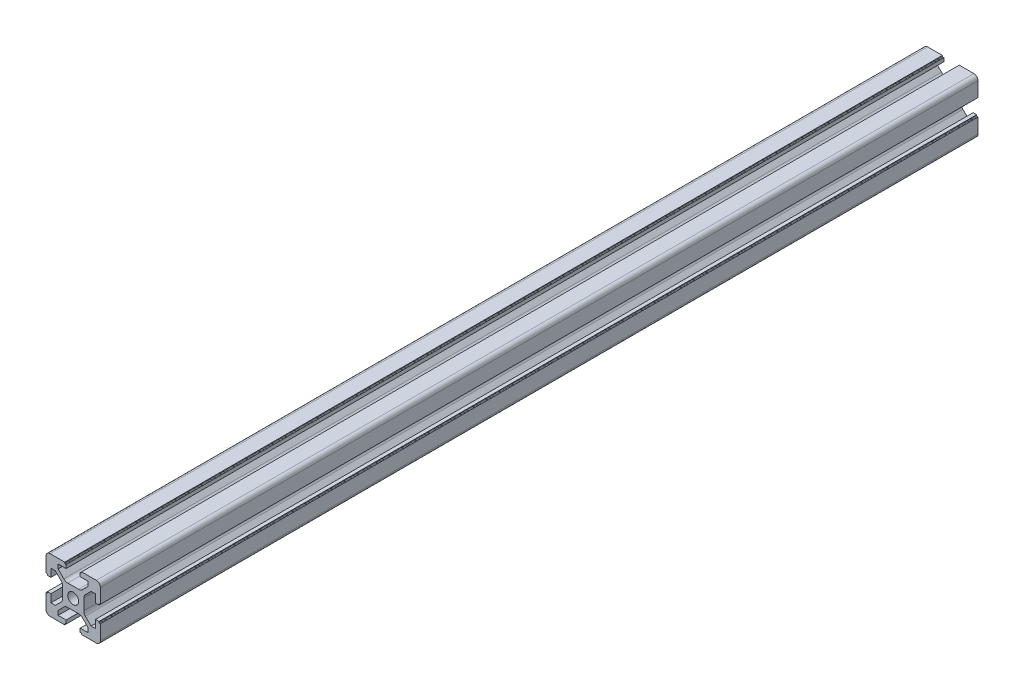
SolidWorks part; units mm, degrees
ref_plane "Спереди" through (0, 0, 0) normal (0, 0, 1) x (1, 0, 0)
ref_plane "Сверху" through (0, 0, 0) normal (0, 1, 0) x (1, 0, 0)
ref_plane "Справа" through (0, 0, 0) normal (1, 0, 0) x (0, 0, -1)
sketch "Sketch1" plane through (0, 0, 0) normal (0, 0, 1) x (1, 0, 0)
  line L0 (0, 10) -> (0, -10) construction
  line L1 (-10, -10) -> (10, -10) construction
  line L2 (-10, -10) -> (-10, 10) construction
  line L3 (-10, 10) -> (10, 10) construction
  line L4 (10, -10) -> (10, 10) construction
  line L5 (-10, -10) -> (10, 10) construction
  line L6 (-10, 10) -> (10, -10) construction
  line L7 (-10, 0) -> (10, 0) construction
  line L8 (0, 3.9) -> (-2.0109, 3.9)
  line L9 (-3.4251, 4.4858) -> (-5.5393, 6.6)
  line L10 (-5.5393, 6.6) -> (-5.5393, 8.2)
  line L11 (-5.5393, 8.2) -> (-2.6, 8.2)
  line L12 (-2.6, 8.2) -> (-2.6, 9.5)
  line L13 (-2.6, 9.5) -> (-2.9, 9.5)
  line L14 (-3.1, 9.7) -> (-3.1, 10)
  line L15 (-3.1, 10) -> (-8.5, 10)
  line L16 (-10, 3.1) -> (-10, 8.5)
  line L17 (-9.7, 3.1) -> (-10, 3.1)
  line L18 (-9.5, 2.6) -> (-9.5, 2.9)
  line L19 (-8.2, 2.6) -> (-9.5, 2.6)
  line L20 (-8.2, 5.5393) -> (-8.2, 2.6)
  line L21 (-6.6, 5.5393) -> (-8.2, 5.5393)
  line L22 (-4.4858, 3.4251) -> (-6.6, 5.5393)
  line L23 (-3.9, 0) -> (-3.9, 2.0109)
  line L24 (3.9, 0) -> (3.9, 2.0109)
  line L25 (4.4858, 3.4251) -> (6.6, 5.5393)
  line L26 (6.6, 5.5393) -> (8.2, 5.5393)
  line L27 (8.2, 5.5393) -> (8.2, 2.6)
  line L28 (8.2, 2.6) -> (9.5, 2.6)
  line L29 (9.5, 2.6) -> (9.5, 2.9)
  line L30 (9.7, 3.1) -> (10, 3.1)
  line L31 (10, 3.1) -> (10, 8.5)
  line L32 (3.1, 10) -> (8.5, 10)
  line L33 (3.1, 9.7) -> (3.1, 10)
  line L34 (2.6, 9.5) -> (2.9, 9.5)
  line L35 (2.6, 8.2) -> (2.6, 9.5)
  line L36 (5.5393, 8.2) -> (2.6, 8.2)
  line L37 (5.5393, 6.6) -> (5.5393, 8.2)
  line L38 (3.4251, 4.4858) -> (5.5393, 6.6)
  line L39 (0, 3.9) -> (2.0109, 3.9)
  line L40 (0, -3.9) -> (2.0109, -3.9)
  line L41 (3.4251, -4.4858) -> (5.5393, -6.6)
  line L42 (5.5393, -6.6) -> (5.5393, -8.2)
  line L43 (5.5393, -8.2) -> (2.6, -8.2)
  line L44 (2.6, -8.2) -> (2.6, -9.5)
  line L45 (2.6, -9.5) -> (2.9, -9.5)
  line L46 (3.1, -9.7) -> (3.1, -10)
  line L47 (3.1, -10) -> (8.5, -10)
  line L48 (10, -3.1) -> (10, -8.5)
  line L49 (9.7, -3.1) -> (10, -3.1)
  line L50 (9.5, -2.6) -> (9.5, -2.9)
  line L51 (8.2, -2.6) -> (9.5, -2.6)
  line L52 (8.2, -5.5393) -> (8.2, -2.6)
  line L53 (6.6, -5.5393) -> (8.2, -5.5393)
  line L54 (4.4858, -3.4251) -> (6.6, -5.5393)
  line L55 (3.9, 0) -> (3.9, -2.0109)
  line L56 (-3.9, 0) -> (-3.9, -2.0109)
  line L57 (-4.4858, -3.4251) -> (-6.6, -5.5393)
  line L58 (-6.6, -5.5393) -> (-8.2, -5.5393)
  line L59 (-8.2, -5.5393) -> (-8.2, -2.6)
  line L60 (-8.2, -2.6) -> (-9.5, -2.6)
  line L61 (-9.5, -2.6) -> (-9.5, -2.9)
  line L62 (-9.7, -3.1) -> (-10, -3.1)
  line L63 (-10, -3.1) -> (-10, -8.5)
  line L64 (-3.1, -10) -> (-8.5, -10)
  line L65 (-3.1, -9.7) -> (-3.1, -10)
  line L66 (-2.6, -9.5) -> (-2.9, -9.5)
  line L67 (-2.6, -8.2) -> (-2.6, -9.5)
  line L68 (-5.5393, -8.2) -> (-2.6, -8.2)
  line L69 (-5.5393, -6.6) -> (-5.5393, -8.2)
  line L70 (-3.4251, -4.4858) -> (-5.5393, -6.6)
  line L71 (0, -3.9) -> (-2.0109, -3.9)
  circle A0 centre (0, 0) radius 2
  arc A1 (-8.5, 10) -> (-10, 8.5) centre (-8.5, 8.5) ccw
  arc A2 (-2.0109, 3.9) -> (-3.4251, 4.4858) centre (-2.0109, 5.9) cw
  arc A3 (-2.9, 9.5) -> (-3.1, 9.7) centre (-2.9, 9.7) cw
  arc A4 (-9.5, 2.9) -> (-9.7, 3.1) centre (-9.7, 2.9) ccw
  arc A5 (-3.9, 2.0109) -> (-4.4858, 3.4251) centre (-5.9, 2.0109) ccw
  arc A6 (10, 8.5) -> (8.5, 10) centre (8.5, 8.5) ccw
  arc A7 (3.9, 2.0109) -> (4.4858, 3.4251) centre (5.9, 2.0109) cw
  arc A8 (9.5, 2.9) -> (9.7, 3.1) centre (9.7, 2.9) cw
  arc A9 (2.9, 9.5) -> (3.1, 9.7) centre (2.9, 9.7) ccw
  arc A10 (2.0109, 3.9) -> (3.4251, 4.4858) centre (2.0109, 5.9) ccw
  arc A11 (8.5, -10) -> (10, -8.5) centre (8.5, -8.5) ccw
  arc A12 (2.0109, -3.9) -> (3.4251, -4.4858) centre (2.0109, -5.9) cw
  arc A13 (2.9, -9.5) -> (3.1, -9.7) centre (2.9, -9.7) cw
  arc A14 (9.5, -2.9) -> (9.7, -3.1) centre (9.7, -2.9) ccw
  arc A15 (3.9, -2.0109) -> (4.4858, -3.4251) centre (5.9, -2.0109) ccw
  arc A16 (-10, -8.5) -> (-8.5, -10) centre (-8.5, -8.5) ccw
  arc A17 (-3.9, -2.0109) -> (-4.4858, -3.4251) centre (-5.9, -2.0109) cw
  arc A18 (-9.5, -2.9) -> (-9.7, -3.1) centre (-9.7, -2.9) cw
  arc A19 (-2.9, -9.5) -> (-3.1, -9.7) centre (-2.9, -9.7) ccw
  arc A20 (-2.0109, -3.9) -> (-3.4251, -4.4858) centre (-2.0109, -5.9) ccw
  point P0 (0, 0)
  point P42 (0, 0)
  point P70 (0, 0)
  point P98 (0, 0)
  point P126 (0, 0)
  dimension "D3" = 4
  dimension "D4" = 3
  dimension "D12" = 2
  dimension "D13" = 0.2
  dimension "D1" = 20
  dimension "D2" = 20
  dimension "D5" = 5.2
  dimension "D6" = 6.2
  dimension "D7" = 1.8
  dimension "D8" = 0.5
  dimension "D9" = 3.4
  dimension "D10" = 1.5
  dimension "D11" = 6.1
  dimension "D14" = 4
extrude "Extrude1" add sketch "Sketch1" along normal blind 323
